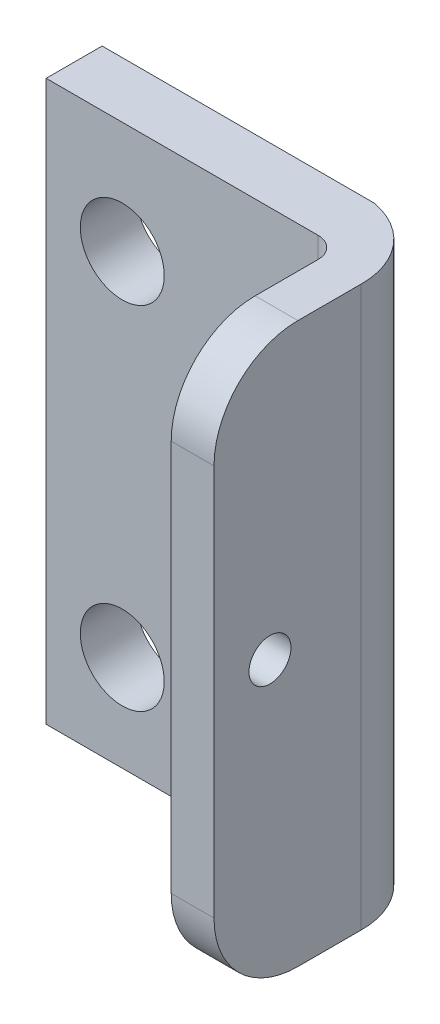
SolidWorks part; units mm, degrees
ref_plane "Front Plane" through (0, 0, 0) normal (0, 0, 1) x (1, 0, 0)
ref_plane "Top Plane" through (0, 0, 0) normal (0, 1, 0) x (1, 0, 0)
ref_plane "Right Plane" through (0, 0, 0) normal (1, 0, 0) x (0, 0, -1)
sketch "Sketch1" plane through (0, 0, 0) normal (0, 0, 1) x (1, 0, 0)
  line L0 (0, 0) -> (9.72, 0)
  line L2 (0, 0) -> (0, 20)
  line L3 (0, 20) -> (9.72, 20)
  line L5 (4.86, 20) -> (4.86, 0) construction
  line L6 (0, 10) -> (9.72, 10) construction
  line L7 (9.72, 0) -> (9.72, 10)
  line L8 (9.72, 20) -> (9.72, 10)
  circle A0 centre (2.72, 16) radius 1.5
  circle A1 centre (2.72, 3.43) radius 1.5
  point P380 (4.86, 10)
  dimension "D2" = 3
  dimension "D3" = 3
  dimension "D1" = 12.57
  dimension "D5" = 4
  dimension "D6" = 2.72
extrude "Boss-Extrude1" add sketch "Sketch1" along normal blind 2
sketch "Sketch2" plane through (0, 0, 0) normal (0, -1, 0) x (1, 0, 0)
  line L0 (9.72, 2) -> (9.72, 0)
  line L1 (11.9997, 2.75) -> (10.47, 2.75)
  line L2 (0, 2) -> (9.72, 2) construction
  arc A0 (9.72, 0) -> (11.9997, 2.75) centre (9.25, 2.7095) ccw
  arc A2 (9.72, 2) -> (10.47, 2.75) centre (9.72, 2.75) ccw
  dimension "D1" = 5.5
  dimension "D3" = 1.5
  dimension "D2" = 0.47
  dimension "D4" = 0.75
  dimension "D5" = 0.75
extrude "Boss-Extrude2" add sketch "Sketch2" against normal blind 20
ref_plane "Plane1" through (12, 0, 0) normal (1, 0, 0) x (0, 0, -1)
sketch "Sketch3" plane through (12, 0, 0) normal (1, 0, 0) x (0, 0, -1)
  line L0 (-2.75, 20) -> (-5, 20)
  line L1 (-8, 17) -> (-8, 3)
  line L2 (-5, 0) -> (-2.75, 0)
  line L3 (-2.75, 20) -> (-2.75, 0)
  line L4 (0, 0) -> (0, 20) construction
  arc A0 (-8, 3) -> (-5, 0) centre (-5, 3) ccw
  arc A1 (-5, 20) -> (-8, 17) centre (-5, 17) ccw
  circle A2 centre (-6, 10) radius 0.75
  dimension "D2" = 3
  dimension "D3" = 1.5
  dimension "D1" = 8
  dimension "D4" = 2
  dimension "D5" = 10
extrude "Boss-Extrude3" add sketch "Sketch3" against normal up to vertex (1.53 mm away)
